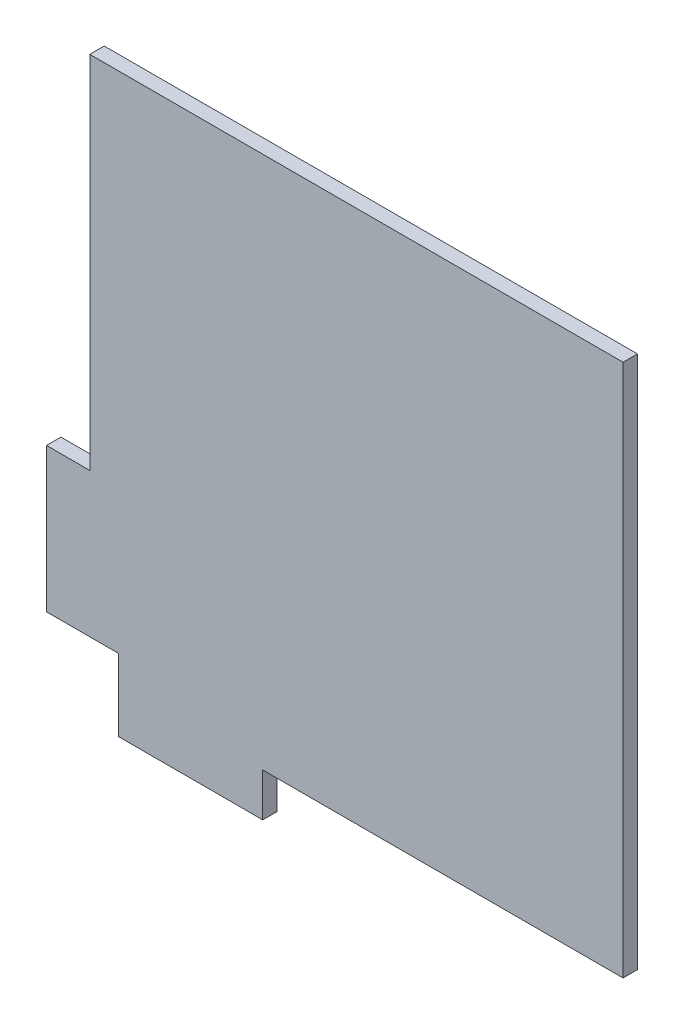
SolidWorks part; units mm, degrees
material "PBT General Purpose"
ref_plane "Front Plane" through (0, 0, 0) normal (0, 0, 1) x (1, 0, 0)
ref_plane "Top Plane" through (0, 0, 0) normal (0, 1, 0) x (1, 0, 0)
ref_plane "Right Plane" through (0, 0, 0) normal (1, 0, 0) x (0, 0, -1)
sketch "Sketch1" plane through (0, 0, 0) normal (0, 0, 1) x (1, 0, 0)
  line L2 (0, 0) -> (0, 3.7)
  line L5 (-2.5, 0) -> (0, 0)
  line L6 (-2.5, 0) -> (-2.5, -0.3)
  line L7 (-2.5, -0.3) -> (-3.5, -0.3)
  line L8 (-3.5, -0.3) -> (-3.5, 0.2)
  line L9 (-3.5, 0.2) -> (-4, 0.2)
  line L10 (-4, 0.2) -> (-4, 1.2)
  line L11 (-4, 1.2) -> (-3.7, 1.2)
  line L12 (-3.7, 1.2) -> (-3.7, 3.7)
  line L13 (0, 3.7) -> (-3.7, 3.7)
  dimension "D2" = 0.5
  dimension "D3" = 0.5
  dimension "D8" = 2.5
  dimension "D9" = 1
  dimension "D10" = 1
  dimension "D11" = 0.3
  dimension "D12" = 0.3
  dimension "D13" = 2.5
extrude "Boss-Extrude1" add sketch "Sketch1" along normal mid plane 0.1
